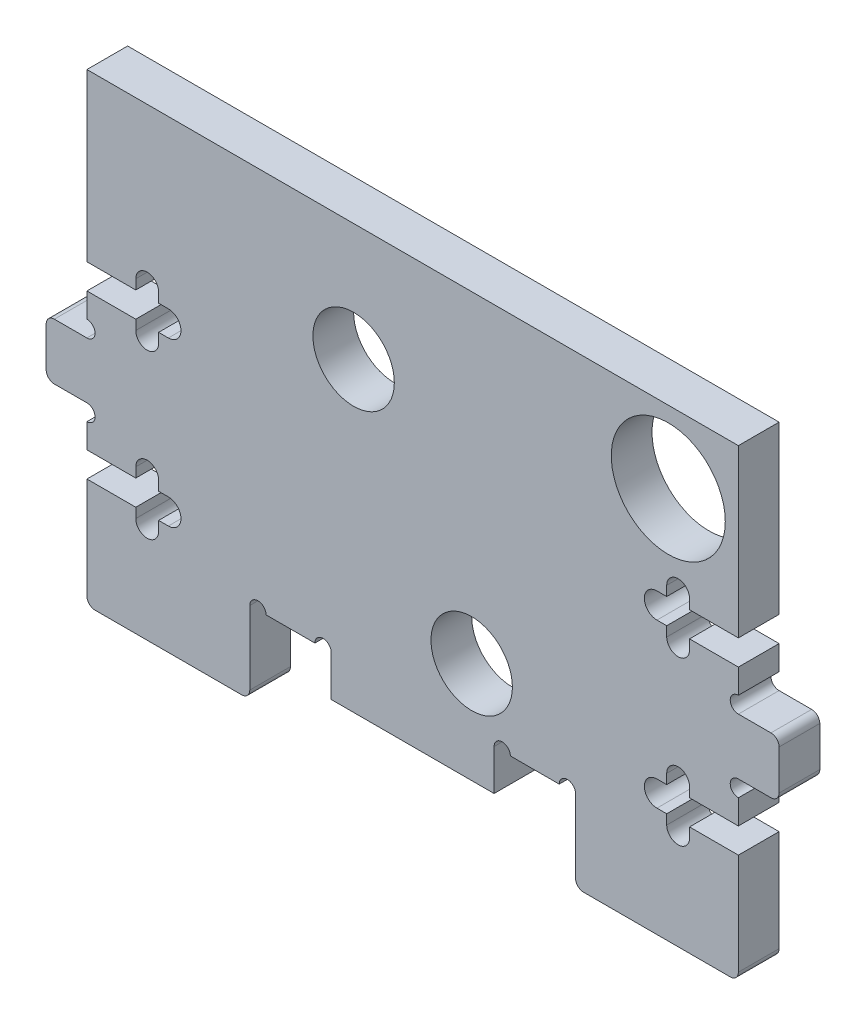
SolidWorks part; units mm, degrees
ref_plane "정면" through (0, 0, 0) normal (0, 0, 1) x (1, 0, 0)
ref_plane "윗면" through (0, 0, 0) normal (0, 1, 0) x (1, 0, 0)
ref_plane "우측면" through (0, 0, 0) normal (1, 0, 0) x (0, 0, -1)
sketch "스케치1" plane through (0, 0, 0) normal (0, 0, 1) x (1, 0, 0)
  line L1 (0, 0) -> (80, 0)
  line L2 (0, 0) -> (0, 52)
  line L3 (0, 52) -> (80, 52)
  line L4 (80, 0) -> (80, 52)
  dimension "D1" = 80
  dimension "D2" = 52
extrude "보스-돌출1" add sketch "스케치1" along normal blind 5
sketch "스케치2" plane through (0, 0, 5) normal (0, 0, 1) x (1, 0, 0)
  line L0 (40, 25) -> (71.3934, 43.125) construction
  line L1 (0, 52) -> (0, 0) construction
  line L3 (0, 0) -> (80, 0) construction
  circle A0 centre (71.3934, 43.125) radius 7
  dimension "D2" = 14
  dimension "D1" = 40
  dimension "D3" = 25
  dimension "D4" = 30
  dimension "D5" = 36.25
extrude "컷-돌출1" cut sketch "스케치2" against normal blind 5
sketch "스케치4" plane through (0, 0, 5) normal (0, 0, 1) x (1, 0, 0)
  line L0 (80, 0) -> (80, 52) construction
  line L1 (80, 42) -> (85, 42)
  line L2 (80, 42) -> (80, 32)
  line L3 (80, 32) -> (85, 32)
  line L4 (85, 42) -> (85, 32)
  line L6 (80, 20) -> (85, 20)
  line L7 (80, 20) -> (80, 10)
  line L8 (80, 10) -> (85, 10)
  line L9 (85, 20) -> (85, 10)
  line L11 (80, 52) -> (0, 52) construction
  line L12 (0, 0) -> (80, 0) construction
  line L13 (85, 32) -> (85, 20) construction
  line L14 (40, 52) -> (40, 0) construction
  line L15 (0, 42) -> (-5, 42)
  line L16 (0, 42) -> (0, 32)
  line L17 (-5, 42) -> (-5, 32)
  line L18 (0, 32) -> (-5, 32)
  line L19 (0, 20) -> (-5, 20)
  line L20 (0, 20) -> (0, 10)
  line L21 (-5, 20) -> (-5, 10)
  line L22 (0, 10) -> (-5, 10)
  dimension "D1" = 10
  dimension "D2" = 10
  dimension "D3" = 10
  dimension "D4" = 10
  dimension "D5" = 5
extrude "보스-돌출2" [suppressed] add sketch "스케치4" against normal blind 5
sketch "스케치5" [suppressed] plane through (0, 0, 5) normal (0, 0, 1) x (1, 0, 0)
  line L0 (70, 42) -> (65, 42) construction
  line L1 (65, 32) -> (70, 32) construction
  line L2 (70, 20) -> (65, 20) construction
  line L3 (65, 10) -> (70, 10) construction
  line L4 (32.5, 52) -> (32.5, 0) construction
  line L5 (65, 52) -> (0, 52) construction
  line L6 (0, 0) -> (65, 0) construction
  circle A0 centre (66, 42) radius 1
  circle A1 centre (66, 32) radius 1
  circle A2 centre (66.0364, 20) radius 1
  circle A3 centre (66, 10) radius 1
  circle A4 centre (-1, 10) radius 1
  circle A5 centre (-1.0364, 20) radius 1
  circle A6 centre (-1, 32) radius 1
  circle A7 centre (-1, 42) radius 1
  dimension "D1" = 2
extrude "컷-돌출2" [suppressed] cut sketch "스케치5" against normal blind 5
sketch "스케치6" plane through (0, 0, 5) normal (0, 0, 1) x (1, 0, 0)
  line L0 (0, 31.55) -> (6, 31.55)
  line L1 (0, 31.55) -> (0, 28.45)
  line L2 (0, 28.45) -> (6, 28.45)
  line L3 (10, 31.55) -> (10, 28.45) construction
  line L4 (8.8, 28.45) -> (10, 28.45)
  line L5 (6, 31.55) -> (6, 32.75)
  line L6 (6, 32.75) -> (8.8, 32.75) construction
  line L7 (8.8, 32.75) -> (8.8, 31.55)
  line L8 (8.8, 28.45) -> (8.8, 27.25)
  line L9 (8.8, 27.25) -> (6, 27.25) construction
  line L10 (8.8, 31.55) -> (10, 31.55)
  line L11 (6, 27.25) -> (6, 28.45)
  line L12 (6, 31.55) -> (6, 28.45) construction
  line L13 (8.8, 31.55) -> (8.8, 28.45) construction
  line L14 (6, 28.45) -> (8.8, 28.45) construction
  line L15 (8.8, 31.55) -> (6, 31.55) construction
  line L16 (16.1272, 30) -> (10, 30) construction
  line L17 (0, 11.55) -> (6, 11.55)
  line L18 (0, 11.55) -> (0, 8.45)
  line L19 (0, 8.45) -> (6, 8.45)
  line L20 (10, 11.55) -> (10, 8.45) construction
  line L21 (8.8, 8.45) -> (10, 8.45)
  line L22 (6, 11.55) -> (6, 12.75)
  line L23 (6, 12.75) -> (8.8, 12.75) construction
  line L24 (8.8, 12.75) -> (8.8, 11.55)
  line L25 (8.8, 8.45) -> (8.8, 7.25)
  line L26 (8.8, 7.25) -> (6, 7.25) construction
  line L27 (8.8, 11.55) -> (10, 11.55)
  line L28 (6, 7.25) -> (6, 8.45)
  line L29 (6, 11.55) -> (6, 8.45) construction
  line L30 (8.8, 11.55) -> (8.8, 8.45) construction
  line L31 (6, 8.45) -> (8.8, 8.45) construction
  line L32 (8.8, 11.55) -> (6, 11.55) construction
  line L33 (16.1272, 10) -> (10, 10) construction
  line L34 (16.1272, 30) -> (16.1272, 10) construction
  line L35 (0, 0) -> (80, 0) construction
  line L36 (40, 52) -> (40, 0) construction
  line L37 (80, 52) -> (0, 52) construction
  line L38 (63.8728, 30) -> (63.8728, 10) construction
  line L39 (63.8728, 10) -> (70, 10) construction
  line L40 (71.2, 11.55) -> (74, 11.55) construction
  line L41 (74, 8.45) -> (71.2, 8.45) construction
  line L42 (71.2, 11.55) -> (71.2, 8.45) construction
  line L43 (74, 11.55) -> (74, 8.45) construction
  line L44 (71.2, 7.25) -> (74, 7.25) construction
  line L45 (74, 12.75) -> (71.2, 12.75) construction
  line L46 (70, 11.55) -> (70, 8.45) construction
  line L47 (63.8728, 30) -> (70, 30) construction
  line L48 (71.2, 31.55) -> (74, 31.55) construction
  line L49 (74, 28.45) -> (71.2, 28.45) construction
  line L50 (71.2, 31.55) -> (71.2, 28.45) construction
  line L51 (74, 31.55) -> (74, 28.45) construction
  line L52 (71.2, 27.25) -> (74, 27.25) construction
  line L53 (74, 32.75) -> (71.2, 32.75) construction
  line L54 (70, 31.55) -> (70, 28.45) construction
  line L55 (74, 7.25) -> (74, 8.45)
  line L56 (71.2, 11.55) -> (70, 11.55)
  line L57 (71.2, 8.45) -> (71.2, 7.25)
  line L58 (71.2, 12.75) -> (71.2, 11.55)
  line L59 (74, 11.55) -> (74, 12.75)
  line L60 (71.2, 8.45) -> (70, 8.45)
  line L61 (80, 8.45) -> (74, 8.45)
  line L62 (80, 11.55) -> (80, 8.45)
  line L63 (80, 11.55) -> (74, 11.55)
  line L64 (74, 27.25) -> (74, 28.45)
  line L65 (71.2, 31.55) -> (70, 31.55)
  line L66 (71.2, 28.45) -> (71.2, 27.25)
  line L67 (71.2, 32.75) -> (71.2, 31.55)
  line L68 (74, 31.55) -> (74, 32.75)
  line L69 (71.2, 28.45) -> (70, 28.45)
  line L70 (80, 28.45) -> (74, 28.45)
  line L71 (80, 31.55) -> (80, 28.45)
  line L72 (80, 31.55) -> (74, 31.55)
  arc A0 (8.8, 32.75) -> (6, 32.75) centre (7.4, 32.75) ccw
  arc A1 (6, 27.25) -> (8.8, 27.25) centre (7.4, 27.25) ccw
  arc A2 (10, 28.45) -> (10, 31.55) centre (10, 30) ccw
  arc A3 (8.8, 12.75) -> (6, 12.75) centre (7.4, 12.75) ccw
  arc A4 (6, 7.25) -> (8.8, 7.25) centre (7.4, 7.25) ccw
  arc A5 (10, 8.45) -> (10, 11.55) centre (10, 10) ccw
  arc A6 (70, 8.45) -> (70, 11.55) centre (70, 10) cw
  arc A7 (74, 7.25) -> (71.2, 7.25) centre (72.6, 7.25) cw
  arc A8 (71.2, 12.75) -> (74, 12.75) centre (72.6, 12.75) cw
  arc A9 (70, 28.45) -> (70, 31.55) centre (70, 30) cw
  arc A10 (74, 27.25) -> (71.2, 27.25) centre (72.6, 27.25) cw
  arc A11 (71.2, 32.75) -> (74, 32.75) centre (72.6, 32.75) cw
  dimension "D1" = 3.1
  dimension "D2" = 10
  dimension "D3" = 5.5
  dimension "D4" = 2.8
  dimension "D5" = 3.1
  dimension "D6" = 10
  dimension "D7" = 5.5
  dimension "D8" = 2.8
  dimension "D9" = 20
  dimension "D10" = 10
extrude "컷-돌출3" cut sketch "스케치6" against normal blind 10
sketch "스케치7" plane through (0, 0, 5) normal (0, 0, 1) x (1, 0, 0)
  line L0 (40, 0) -> (40, 25) construction
  line L1 (0, 0) -> (80, 0) construction
  line L2 (0, 28.45) -> (0, 11.55) construction
  line L3 (47.25, 12.4426) -> (40, 25) construction
  line L4 (40, 25) -> (32.75, 37.5574) construction
  circle A0 centre (32.75, 37.5574) radius 5
  circle A1 centre (47.25, 12.4426) radius 5
  dimension "D4" = 10
  dimension "D1" = 40
  dimension "D2" = 25
  dimension "D3" = 30
  dimension "D5" = 29
extrude "컷-돌출4" cut sketch "스케치7" against normal blind 10
sketch "스케치10" plane through (0, 0, 0) normal (0, 0, -1) x (-1, 0, 0)
  line L0 (0, 0) -> (-80, 0) construction
  line L1 (-20, 5) -> (-30, 5)
  line L2 (-20, 5) -> (-20, 0)
  line L3 (-20, 0) -> (-30, 0)
  line L4 (-30, 5) -> (-30, 0)
  line L5 (-30, 5) -> (-30, 0) construction
  line L6 (-50, 5) -> (-50, 0) construction
  line L7 (-50, 0) -> (-60, 0)
  line L8 (-50, 0) -> (-50, 5)
  line L9 (-50, 5) -> (-60, 5)
  line L10 (-60, 0) -> (-60, 5)
extrude "컷-돌출5" cut sketch "스케치10" against normal blind 10
sketch "스케치11" plane through (0, 0, 5) normal (0, 0, 1) x (1, 0, 0)
  line L0 (50, 5) -> (60, 5) construction
  line L1 (20, 5) -> (30, 5) construction
  circle A0 centre (59, 5) radius 1
  circle A1 centre (51, 5) radius 1
  circle A2 centre (29, 5) radius 1
  circle A3 centre (21, 5) radius 1
  dimension "D1" = 2
extrude "컷-돌출6" cut sketch "스케치11" against normal blind 10
sketch "스케치12" plane through (0, 0, 5) normal (0, 0, 1) x (1, 0, 0)
  line L0 (80, 11.55) -> (80, 28.45) construction
  line L1 (80, 23.45) -> (85, 23.45)
  line L2 (80, 23.45) -> (80, 16.55)
  line L3 (80, 16.55) -> (85, 16.55)
  line L4 (85, 23.45) -> (85, 16.55)
  line L5 (0, 28.45) -> (0, 11.55) construction
  line L6 (0, 23.45) -> (-5, 23.45)
  line L7 (0, 23.45) -> (0, 16.55)
  line L8 (0, 16.55) -> (-5, 16.55)
  line L9 (-5, 23.45) -> (-5, 16.55)
  line L10 (74, 28.45) -> (80, 28.45) construction
  line L11 (80, 11.55) -> (74, 11.55) construction
  dimension "D1" = 5
  dimension "D2" = 5
  dimension "D3" = 5
extrude "보스-돌출3" add sketch "스케치12" against normal blind 5
sketch "스케치13" plane through (0, 0, 5) normal (0, 0, 1) x (1, 0, 0)
  line L0 (80, 23.45) -> (80, 28.45) construction
  line L1 (80, 11.55) -> (80, 16.55) construction
  line L2 (0, 16.55) -> (0, 11.55) construction
  line L3 (0, 28.45) -> (0, 23.45) construction
  line L4 (85, 23.45) -> (80, 23.45) construction
  circle A0 centre (80, 24.45) radius 1
  circle A1 centre (80, 15.55) radius 1
  circle A2 centre (0, 15.55) radius 1
  circle A3 centre (0, 24.45) radius 1
  dimension "D1" = 2
extrude "컷-돌출7" cut sketch "스케치13" against normal blind 5
fillet "필렛1" radius 1 4 edges at (85, 16.55, 2.5) (85, 23.45, 2.5) (-5, 16.55, 2.5) (-5, 23.45, 2.5)
sketch "스케치14" plane through (0, 0, 5) normal (0, 0, 1) x (1, 0, 0)
  line L1 (80, 0) -> (60, 0)
  line L2 (80, 0) -> (80, -5)
  line L3 (80, -5) -> (60, -5)
  line L4 (60, 0) -> (60, -5)
  line L5 (0, 0) -> (20, 0)
  line L6 (0, 0) -> (0, -5)
  line L7 (0, -5) -> (20, -5)
  line L8 (20, 0) -> (20, -5)
  dimension "D1" = 5
extrude "보스-돌출4" add sketch "스케치14" against normal blind 5
fillet "필렛2" radius 1 4 edges at (0, -5, 2.5) (20, -5, 2.5) (60, -5, 2.5) (80, -5, 2.5)
